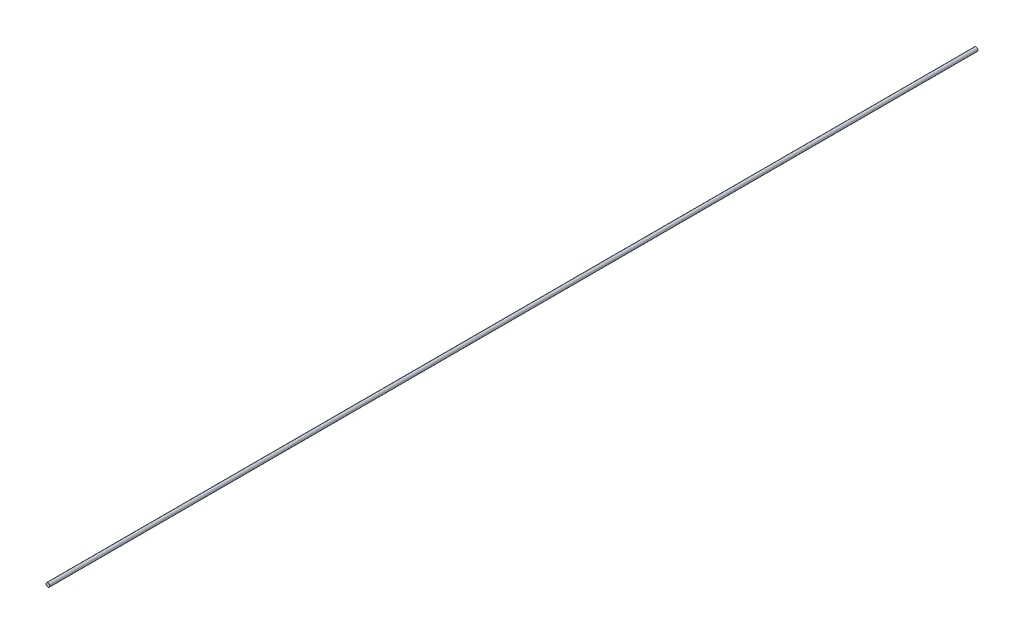
SolidWorks part; units mm, degrees
material "6061 Alloy"
ref_plane "Front" through (0, 0, 0) normal (0, 0, 1) x (1, 0, 0)
ref_plane "Top" through (0, 0, 0) normal (0, 1, 0) x (1, 0, 0)
ref_plane "Right" through (0, 0, 0) normal (1, 0, 0) x (0, 0, -1)
sketch "Sketch1" plane through (0, 0, 0) normal (0, 0, 1) x (1, 0, 0)
  circle A0 centre (0, 0) radius 1.905
  dimension "D1" = 3.81
extrude "Boss-Extrude1" add sketch "Sketch1" along normal blind 914.4
